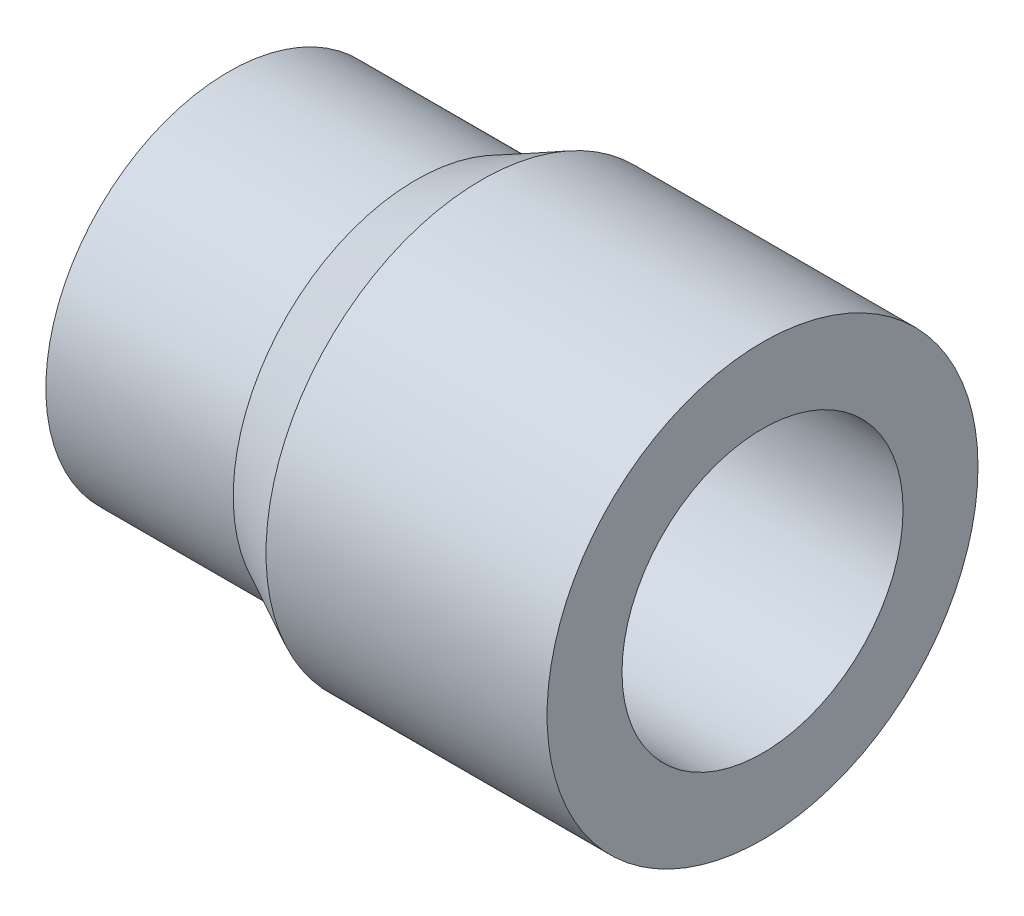
SolidWorks part; units mm, degrees
ref_plane "Alzado" through (0, 0, 0) normal (1, 0, 0) x (0, 1, 0)
ref_plane "Planta" through (0, 0, 0) normal (0, 0, 1) x (0, 1, 0)
ref_plane "Vista lateral" through (0, 0, 0) normal (0, 1, 0) x (-1, 0, 0)
sketch "Croquis1" plane through (0, 0, 0) normal (0, 1, 0) x (-1, 0, 0)
  line L0 (0, 2.3) -> (0, 1.5)
  line L1 (0, 1.5) -> (5.7, 1.5)
  line L2 (5.7, 1.5) -> (5.7, 1.95)
  line L3 (5.7, 1.95) -> (3.7, 1.95)
  line L4 (3.7, 1.95) -> (3, 2.3)
  line L5 (3, 2.3) -> (0, 2.3)
  line L6 (0, 0) -> (5.7, 0) construction
  dimension "D1" = 5.7
  dimension "D2" = 4.6
  dimension "D3" = 3
  dimension "D4" = 3
  dimension "D5" = 3.9
  dimension "D6" = 2
revolve "Revolución1" add sketch "Croquis1" angle 360 about L6
